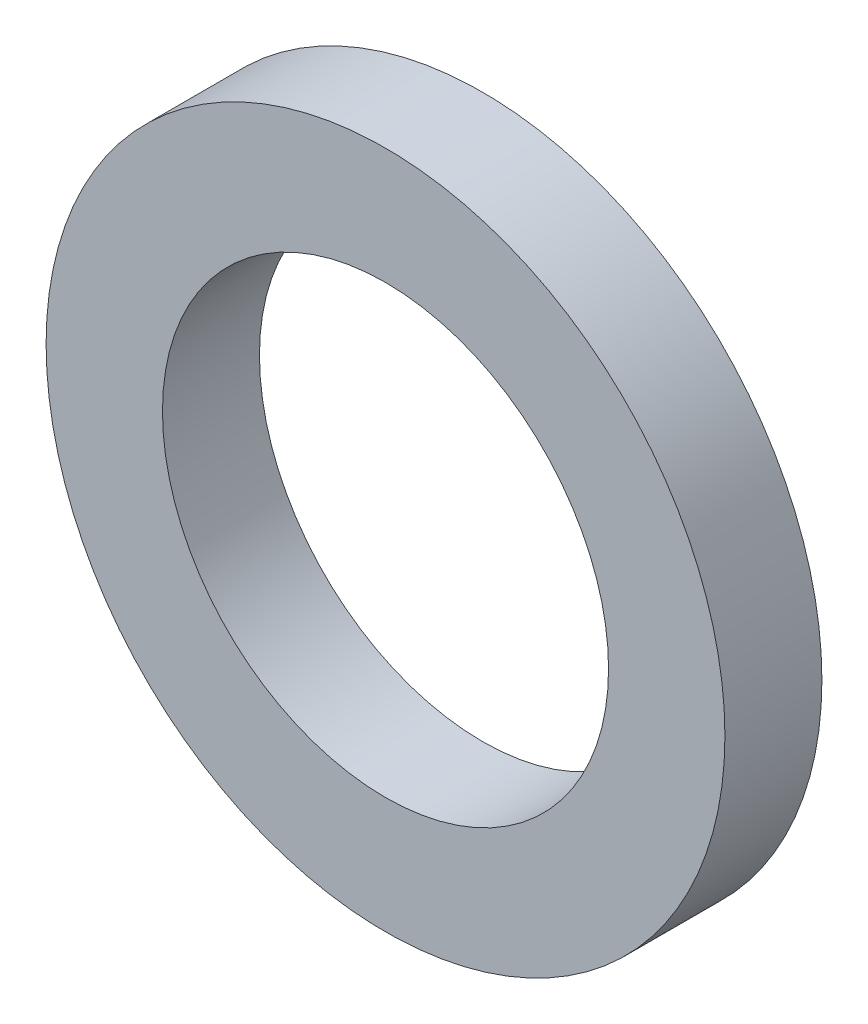
SolidWorks part; units mm, degrees
ref_plane "前视基准面" through (0, 0, 0) normal (0, 0, 1) x (1, 0, 0)
ref_plane "上视基准面" through (0, 0, 0) normal (0, 1, 0) x (1, 0, 0)
ref_plane "右视基准面" through (0, 0, 0) normal (1, 0, 0) x (0, 0, -1)
sketch "草图1" plane through (0, 0, 0) normal (0, 0, 1) x (1, 0, 0)
  circle A0 centre (0, 0) radius 17.5
  circle A1 centre (0, 0) radius 11.5
  dimension "D1" = 35
  dimension "D2" = 23
extrude "凸台-拉伸1" add sketch "草图1" along normal blind 5
